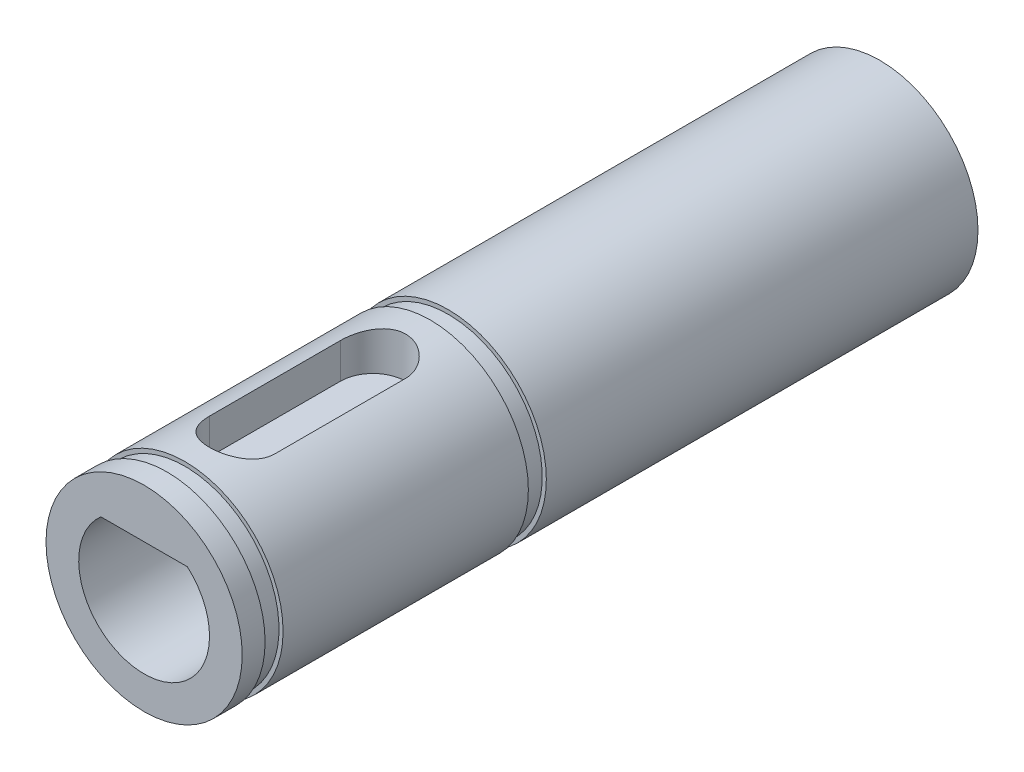
SolidWorks part; units mm, degrees
material "AISI 304"
ref_plane "Plano frontal" through (0, 0, 0) normal (0, 0, 1) x (1, 0, 0)
ref_plane "Plano superior" through (0, 0, 0) normal (0, 1, 0) x (1, 0, 0)
ref_plane "Plano direito" through (0, 0, 0) normal (1, 0, 0) x (0, 0, -1)
sketch "Esboço1" plane through (0, 0, 0) normal (0, 0, 1) x (1, 0, 0)
  line L0 (-2.6458, 3) -> (2.6458, 3)
  arc A0 (-2.6458, 3) -> (2.6458, 3) centre (0, 0) ccw
  circle A1 centre (0, 0) radius 6
  dimension "D1" = 4
  dimension "D3" = 12
  dimension "D2" = 3
extrude "Ressalto-extrusão1" add sketch "Esboço1" along normal blind 45
ref_plane "Plano1" through (0, 6, 0) normal (0, 1, 0) x (1, 0, 0)
sketch "Esboço2" plane through (0, 6, 0) normal (0, 1, 0) x (1, 0, 0)
  line L0 (0, -39) -> (0, -31) construction
  line L1 (-2, -39) -> (-2, -31)
  line L2 (2, -39) -> (2, -31)
  line L3 (-6, -45) -> (6, -45) construction
  arc A0 (-2, -39) -> (2, -39) centre (0, -39) ccw
  arc A1 (2, -31) -> (-2, -31) centre (0, -31) ccw
  point P3 (0, -35)
  point P11 (0, -35)
  dimension "D3" = 2
  dimension "D1" = 10
  dimension "D2" = 8
extrude "Corte-extrusão1" cut sketch "Esboço2" against normal blind 2.5
sketch "Esboço3" plane through (0, 0, 0) normal (1, 0, 0) x (0, 0, -1)
  line L0 (0, 6) -> (-29, 6) construction
  line L1 (-27.5, 6) -> (-26.4, 6)
  line L2 (-27.5, 6) -> (-27.5, 5.75)
  line L3 (-27.5, 5.75) -> (-26.4, 5.75)
  line L4 (-26.4, 6) -> (-26.4, 5.75)
  line L5 (0, -6) -> (0, 6) construction
  line L6 (-41, 6) -> (-45, 6) construction
  line L7 (-43.6, 6) -> (-42.5, 6)
  line L8 (-43.6, 6) -> (-43.6, 5.75)
  line L9 (-43.6, 5.75) -> (-42.5, 5.75)
  line L10 (-42.5, 6) -> (-42.5, 5.75)
  line L11 (0, 0) -> (-45, 0) construction
  line L12 (-45, 6) -> (-45, -6) construction
  point P14 (-42.5, 5.875)
  dimension "D1" = 1.1
  dimension "D2" = 0.25
  dimension "D3" = 26.4
  dimension "D4" = 0.25
  dimension "D5" = 1.1
  dimension "D6" = 42.5
revolve "Corte-Revolução1" cut sketch "Esboço3" angle 360 about L11
